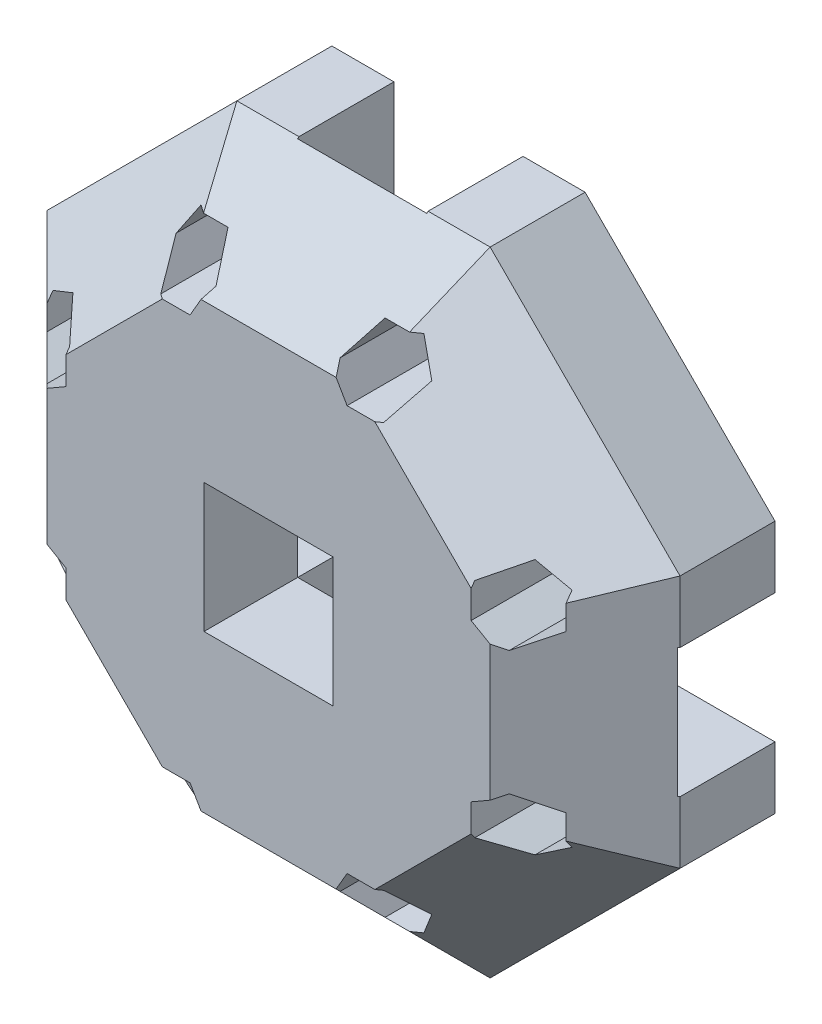
SolidWorks part; units mm, degrees
ref_plane "정면" through (0, 0, 0) normal (0, 0, 1) x (1, 0, 0)
ref_plane "윗면" through (0, 0, 0) normal (0, 1, 0) x (1, 0, 0)
ref_plane "우측면" through (0, 0, 0) normal (1, 0, 0) x (0, 0, -1)
sketch "스케치1" plane through (0, 0, 0) normal (0, 0, 1) x (1, 0, 0)
  line L0 (-20, 50) -> (-50, 20)
  line L1 (-50, 20) -> (-50, -20)
  line L2 (-50, -20) -> (-20, -50)
  line L3 (-20, -50) -> (20, -50)
  line L4 (20, -50) -> (50, -20)
  line L5 (50, -20) -> (50, 20)
  line L6 (50, 20) -> (20, 50)
  line L7 (20, 50) -> (-20, 50)
  line L8 (-50, 0) -> (50, 0) construction
  line L9 (0, 50) -> (0, -50) construction
  dimension "D1" = 40
  dimension "D2" = 135
  dimension "D3" = 100
  dimension "D4" = 100
extrude "보스-돌출1" add sketch "스케치1" along normal blind 30
chamfer "모따기1" distance 15 angle 45 8 edges at (35, 35, 30) (50, 0, 30) (35, -35, 30) (0, -50, 30) (-35, -35, 30) (-50, 0, 30) (-35, 35, 30) (0, 50, 30)
sketch "스케치2" plane through (50, 0, 0) normal (1, 0, 0) x (0, 0, -1)
  line L0 (0, -20) -> (0, 20) construction
  line L1 (0, 10.2) -> (-15.2, 10.2)
  line L2 (0, 10.2) -> (0, -10.2)
  line L3 (0, -10.2) -> (-15.2, -10.2)
  line L4 (-15.2, 10.2) -> (-15.2, -10.2)
  dimension "D1" = 10.2
  dimension "D2" = 10.2
  dimension "D3" = 15.2
extrude "컷-돌출1" cut sketch "스케치2" against normal blind 50
sketch "스케치3" plane through (0, 0, 30) normal (0, 0, 1) x (1, 0, 0)
  circle A0 centre (36.5, -15) radius 2.55
  circle A1 centre (36.5, 15) radius 2.55
  circle A2 centre (-15, -36.5) radius 2.55
  circle A3 centre (15, -36.5) radius 2.55
  circle A4 centre (-36.5, 15) radius 2.55
  circle A5 centre (-36.5, -15) radius 2.55
  circle A6 centre (15, 36.5) radius 2.55
  circle A7 centre (-15, 36.5) radius 2.55
  point P4 (-45.3766, -20)
  point P6 (0, 0)
  point P20 (0, 0)
  dimension "D3" = 5.1
  dimension "D5" = 5.1
  dimension "D1" = 36.5
  dimension "D2" = 15
  dimension "D4" = 15
  dimension "D6" = 36.5
  dimension "D7" = 4
extrude "컷-돌출2" cut sketch "스케치3" against normal through all
sketch "스케치4" plane through (0, 0, 30) normal (0, 0, 1) x (1, 0, 0)
  line L0 (-12.4019, -32) -> (-17.5981, -32)
  line L1 (32, -12.4019) -> (32, -17.5981)
  line L2 (32, -17.5981) -> (36.5, -20.1962)
  line L3 (36.5, -20.1962) -> (41, -17.5981)
  line L4 (41, -17.5981) -> (41, -12.4019)
  line L5 (41, -12.4019) -> (36.5, -9.8038)
  line L6 (36.5, -9.8038) -> (32, -12.4019)
  line L7 (36.5, 9.8038) -> (41, 12.4019)
  line L8 (41, 12.4019) -> (41, 17.5981)
  line L9 (41, 17.5981) -> (36.5, 20.1962)
  line L10 (36.5, 20.1962) -> (32, 17.5981)
  line L11 (32, 17.5981) -> (32, 12.4019)
  line L12 (32, 12.4019) -> (36.5, 9.8038)
  line L13 (-17.5981, -32) -> (-20.1962, -36.5)
  line L14 (-20.1962, -36.5) -> (-17.5981, -41)
  line L15 (-17.5981, -41) -> (-12.4019, -41)
  line L16 (-12.4019, -41) -> (-9.8038, -36.5)
  line L17 (-9.8038, -36.5) -> (-12.4019, -32)
  line L18 (9.8038, -36.5) -> (12.4019, -41)
  line L19 (12.4019, -41) -> (17.5981, -41)
  line L20 (17.5981, -41) -> (20.1962, -36.5)
  line L21 (20.1962, -36.5) -> (17.5981, -32)
  line L22 (17.5981, -32) -> (12.4019, -32)
  line L23 (12.4019, -32) -> (9.8038, -36.5)
  line L24 (-32, 12.4019) -> (-32, 17.5981)
  line L25 (-32, 17.5981) -> (-36.5, 20.1962)
  line L26 (-36.5, 20.1962) -> (-41, 17.5981)
  line L27 (-41, 17.5981) -> (-41, 12.4019)
  line L28 (-41, 12.4019) -> (-36.5, 9.8038)
  line L29 (-36.5, 9.8038) -> (-32, 12.4019)
  line L30 (-36.5, -9.8038) -> (-41, -12.4019)
  line L31 (-41, -12.4019) -> (-41, -17.5981)
  line L32 (-41, -17.5981) -> (-36.5, -20.1962)
  line L33 (-36.5, -20.1962) -> (-32, -17.5981)
  line L34 (-32, -17.5981) -> (-32, -12.4019)
  line L35 (-32, -12.4019) -> (-36.5, -9.8038)
  line L36 (12.4019, 32) -> (17.5981, 32)
  line L37 (17.5981, 32) -> (20.1962, 36.5)
  line L38 (20.1962, 36.5) -> (17.5981, 41)
  line L39 (17.5981, 41) -> (12.4019, 41)
  line L40 (12.4019, 41) -> (9.8038, 36.5)
  line L41 (9.8038, 36.5) -> (12.4019, 32)
  line L42 (-9.8038, 36.5) -> (-12.4019, 41)
  line L43 (-12.4019, 41) -> (-17.5981, 41)
  line L44 (-17.5981, 41) -> (-20.1962, 36.5)
  line L45 (-20.1962, 36.5) -> (-17.5981, 32)
  line L46 (-17.5981, 32) -> (-12.4019, 32)
  line L47 (-12.4019, 32) -> (-9.8038, 36.5)
  circle A0 centre (36.5, -15) radius 4.5 construction
  circle A1 centre (36.5, 15) radius 4.5 construction
  circle A2 centre (-15, -36.5) radius 4.5 construction
  circle A3 centre (15, -36.5) radius 4.5 construction
  circle A4 centre (-36.5, 15) radius 4.5 construction
  circle A5 centre (-36.5, -15) radius 4.5 construction
  circle A6 centre (15, 36.5) radius 4.5 construction
  circle A7 centre (-15, 36.5) radius 4.5 construction
  point P10 (0, 0)
  point P21 (0, 0)
  point P69 (0, 0)
  dimension "D1" = 9
  dimension "D2" = 9
  dimension "D3" = 4
extrude "컷-돌출3" cut sketch "스케치4" against normal blind 15
sketch "스케치5" plane through (0, 0, 0) normal (0, 1, 0) x (1, 0, 0)
  line L0 (0, 6.9278) -> (0, -50.374) construction
pattern_circular "원형 패턴1" count 4 every 90 about axis through (0, 0, 0) along (0, 0, 1) of "컷-돌출1"
sketch "스케치6" plane through (0, 0, 15.2) normal (0, 0, -1) x (-1, 0, 0)
  line L1 (-10.2, 10.2) -> (10.2, 10.2)
  line L2 (-10.2, 10.2) -> (-10.2, -10.2)
  line L3 (-10.2, -10.2) -> (10.2, -10.2)
  line L4 (10.2, 10.2) -> (10.2, -10.2)
extrude "컷-돌출4" cut sketch "스케치6" against normal through all
